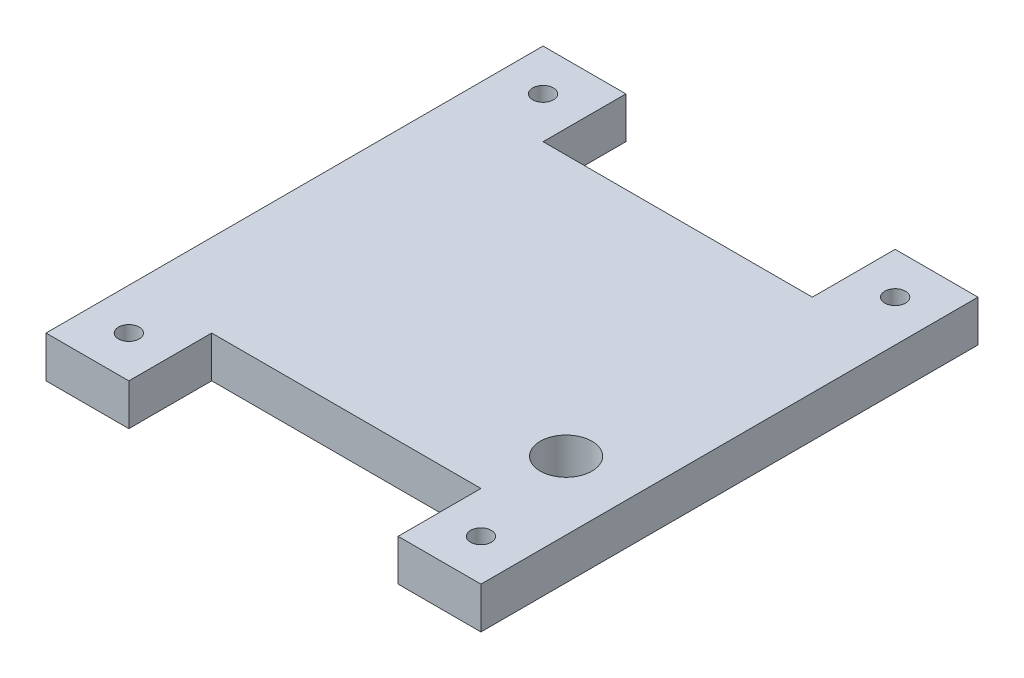
SolidWorks part; units mm, degrees
ref_plane "Front Plane" through (0, 0, 0) normal (0, 0, 1) x (1, 0, 0)
ref_plane "Top Plane" through (0, 0, 0) normal (0, 1, 0) x (1, 0, 0)
ref_plane "Right Plane" through (0, 0, 0) normal (1, 0, 0) x (0, 0, -1)
sketch "Sketch1" plane through (0, 4.2488, 0) normal (0, 1, 0) x (1, 0, 0)
  line L1 (31.9672, 5.5586) -> (10.9672, 5.5586)
  line L2 (31.9672, 5.5586) -> (31.9672, -6.4414)
  line L3 (31.9672, -6.4414) -> (10.9672, -6.4414)
  line L4 (10.9672, 5.5586) -> (10.9672, -6.4414)
  line L10 (10.9672, 11.5586) -> (10.9672, 3.5586)
  line L11 (10.9672, 3.5586) -> (12.9672, 3.5586)
  line L12 (12.9672, -6.4414) -> (12.9672, -4.4414)
  line L13 (12.9672, -4.4414) -> (10.9672, -4.4414)
  line L14 (10.9672, -4.4414) -> (10.9672, -12.4414)
  line L15 (10.9672, -12.4414) -> (14.9672, -12.4414)
  line L16 (14.9672, -12.4414) -> (14.9672, -8.4414)
  line L17 (14.9672, -8.4414) -> (27.9672, -8.4414)
  line L18 (27.9672, -8.4414) -> (27.9672, -12.4414)
  line L19 (27.9672, -12.4414) -> (31.9672, -12.4414)
  line L20 (31.9672, -12.4414) -> (31.9672, -0.4414)
  line L21 (31.9672, -0.4414) -> (29.9672, -0.4414)
  line L22 (29.9672, -0.4414) -> (29.9672, -6.4414)
  line L23 (29.9672, -6.4414) -> (12.9672, -6.4414)
  line L24 (12.9672, -6.4414) -> (12.9672, -4.4414)
  line L25 (12.9672, -4.4414) -> (10.9672, -4.4414)
  line L26 (10.9672, -4.4414) -> (10.9672, -12.4414)
  line L27 (10.9672, -12.4414) -> (14.9672, -12.4414)
  line L28 (14.9672, -12.4414) -> (14.9672, -8.4414)
  line L29 (14.9672, -8.4414) -> (27.9672, -8.4414)
  line L30 (27.9672, -8.4414) -> (27.9672, -12.4414)
  line L31 (27.9672, -12.4414) -> (31.9672, -12.4414)
  line L32 (31.9672, -12.4414) -> (31.9672, -0.4414)
  line L33 (31.9672, -0.4414) -> (29.9672, -0.4414)
  line L34 (29.9672, -0.4414) -> (29.9672, -6.4414)
  line L35 (29.9672, -6.4414) -> (12.9672, -6.4414)
  line L36 (12.9672, 3.5586) -> (12.9672, 5.5586)
  line L37 (12.9672, 5.5586) -> (31.9672, 5.5586)
  line L38 (31.9672, 5.5586) -> (31.9672, 11.5586)
  line L39 (31.9672, 11.5586) -> (27.9672, 11.5586)
  line L40 (27.9672, 11.5586) -> (27.9672, 7.5586)
  line L41 (27.9672, 7.5586) -> (14.9672, 7.5586)
  line L42 (14.9672, 7.5586) -> (14.9672, 11.5586)
  line L43 (14.9672, 11.5586) -> (10.9672, 11.5586)
  line L44 (10.9672, 11.5586) -> (10.9672, 3.5586)
  line L45 (10.9672, 3.5586) -> (12.9672, 3.5586)
  line L46 (12.9672, 3.5586) -> (12.9672, 5.5586)
  line L47 (12.9672, 5.5586) -> (31.9672, 5.5586)
  line L48 (31.9672, 5.5586) -> (31.9672, 11.5586)
  line L49 (31.9672, 11.5586) -> (27.9672, 11.5586)
  line L50 (27.9672, 11.5586) -> (27.9672, 7.5586)
  line L51 (27.9672, 7.5586) -> (14.9672, 7.5586)
  line L52 (14.9672, 7.5586) -> (14.9672, 11.5586)
  line L53 (14.9672, 11.5586) -> (10.9672, 11.5586)
  circle A0 centre (12.9672, -10.4414) radius 0.5 construction
  circle A1 centre (29.9672, -10.4414) radius 0.5 construction
  circle A2 centre (29.9672, 9.5586) radius 0.5 construction
  circle A3 centre (12.9672, 9.5586) radius 0.5 construction
  circle A4 centre (12.9672, -10.4414) radius 0.5
  circle A5 centre (29.9672, -10.4414) radius 0.5
  circle A6 centre (29.9672, 9.5586) radius 0.5
  circle A7 centre (12.9672, 9.5586) radius 0.5
  circle M27 centre (12.9672, -10.4414) radius 0.5
  circle M28 centre (29.9672, -10.4414) radius 0.5
  line M29 (12.9672, -6.4414) -> (12.9672, -4.4414)
  line M30 (12.9672, -4.4414) -> (10.9672, -4.4414)
  line M31 (10.9672, -4.4414) -> (10.9672, -12.4414)
  line M32 (10.9672, -12.4414) -> (14.9672, -12.4414)
  line M33 (14.9672, -12.4414) -> (14.9672, -8.4414)
  line M34 (14.9672, -8.4414) -> (27.9672, -8.4414)
  line M35 (27.9672, -8.4414) -> (27.9672, -12.4414)
  line M36 (27.9672, -12.4414) -> (31.9672, -12.4414)
  line M37 (31.9672, -12.4414) -> (31.9672, -0.4414)
  line M38 (31.9672, -0.4414) -> (29.9672, -0.4414)
  line M39 (29.9672, -0.4414) -> (29.9672, -6.4414)
  line M40 (29.9672, -6.4414) -> (12.9672, -6.4414)
  dimension "D1" = 0
  dimension "D2" = 0
extrude "Boss-Extrude1" add sketch "Sketch1" along normal blind 2 contours L52 L53 L44 L1 L48 L49 L50 L51 A7 A6 | L46 L45 L4 L2 L1 M30 M29 M40 M39 M38 | L3 M37 M40 M31 M32 M33 M34 M35 M36 M28 M27 | L3 M29 M30 M31 | L45 L46 L1 L4 | L3 M37 M38 M39
sketch "Sketch2" plane through (0, 6.2488, 0) normal (0, 1, 0) x (1, 0, 0)
  circle A0 centre (28.6728, -5.0346) radius 1.25
  point P2 (26.6761, -5.1284)
  point P3 (28.8051, -5.3836)
  point P4 (28.6728, -5.0346)
  dimension "D1" = 2.5
extrude "Cut-Extrude1" cut sketch "Sketch2" against normal blind 2
